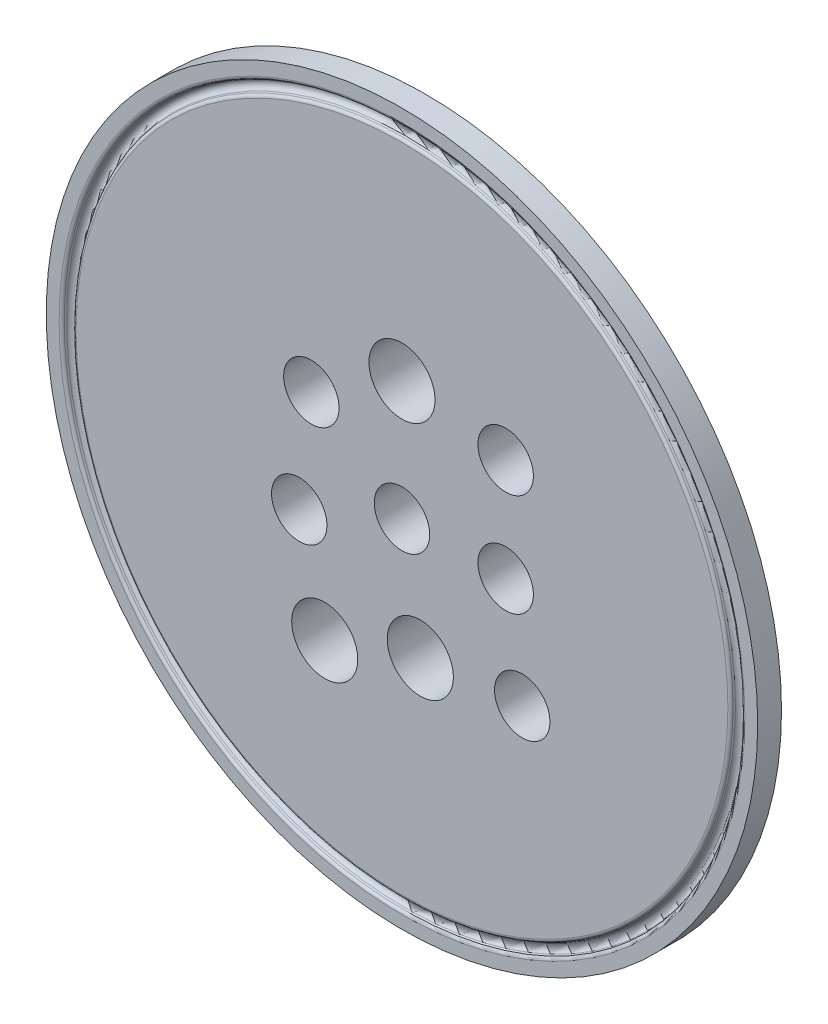
SolidWorks part; units mm, degrees
other "Markup1"
sketch "Sketch3"
ref_plane "Front Plane" through (0, 0, 0) normal (0, 0, 1) x (1, 0, 0)
ref_plane "Top Plane" through (0, 0, 0) normal (0, 1, 0) x (1, 0, 0)
ref_plane "Right Plane" through (0, 0, 0) normal (1, 0, 0) x (0, 0, -1)
sketch "Sketch1" plane through (0, 0, 0) normal (1, 0, 0) x (0, 0, -1)
  line L0 (0, 0) -> (11.0998, 0) construction
  line L1 (0, 0) -> (0, 76.4446)
  line L2 (0, 83.439) -> (5.588, 83.439)
  line L3 (5.588, 83.439) -> (11.0998, 68.2955)
  line L4 (11.0998, 68.2955) -> (11.0998, 0)
  line L5 (0, 80.4258) -> (0, 83.439)
  line L6 (0.4797, 79.701) -> (0.8729, 79.5341)
  line L7 (0.4797, 77.1694) -> (0.8729, 77.3363)
  line L8 (0, 79.9046) -> (0, 76.9658) construction
  line L9 (0, 78.4352) -> (0.4064, 78.4352) construction
  line L10 (0, 0) -> (11.0998, 0)
  arc A0 (0.8729, 77.3363) -> (0.8729, 79.5341) centre (0.4064, 78.4352) ccw
  arc A2 (0, 76.4446) -> (0.4797, 77.1694) centre (0.7874, 76.4446) cw
  arc A3 (0, 80.4258) -> (0.4797, 79.701) centre (0.7874, 80.4258) ccw
  dimension "K" = 1.1938
  dimension "L" = 0.7874
  dimension "I" = 20
  dimension "C" = 136.5909
  dimension "F" = 5.588
  dimension "H" = 0.4064
  dimension "B" = 156.8704
  dimension "A" = 166.878
  dimension "M" = 46
  dimension "N" = 23
  dimension "Length" = 11.0998
revolve "Revolve1" add sketch "Sketch1" angle 360 about L0
sketch "Sketch2" plane through (0, 0, -11.0998) normal (0, 0, -1) x (-1, 0, 0)
  circle A0 centre (0, 0) radius 6.5
  circle A1 centre (0, 0) radius 10.5 construction
  circle A4 centre (0, 27.9766) radius 7.75
  circle A6 centre (-24.3241, 0) radius 6.5
  circle A7 centre (-24.3241, 0) radius 10.5 construction
  circle A10 centre (24.099, -10.1576) radius 6.5
  circle A11 centre (24.099, -10.1576) radius 10.5 construction
  circle A12 centre (-24.3241, 24.0674) radius 6.5
  circle A13 centre (-24.3241, 24.0674) radius 10.5 construction
  circle A14 centre (21.2594, 15.1001) radius 6.5
  circle A15 centre (21.2594, 15.1001) radius 10.5 construction
  circle A16 centre (0, 27.9766) radius 10.5 construction
  circle A17 centre (-4.2973, -26.1492) radius 7.75
  circle A18 centre (-4.2973, -26.1492) radius 10.5 construction
  circle A19 centre (-28.2099, -23.9074) radius 10.5 construction
  circle A20 centre (-28.2099, -23.9074) radius 6.5
  circle A21 centre (18.1208, -33.7713) radius 7.75
  circle A22 centre (18.1208, -33.7713) radius 10.5 construction
  dimension "D3" = 15.5
  dimension "D10" = 13
  dimension "D11" = 21
  dimension "D14" = 21
extrude "Cut-Extrude1" cut sketch "Sketch2" against normal through all
